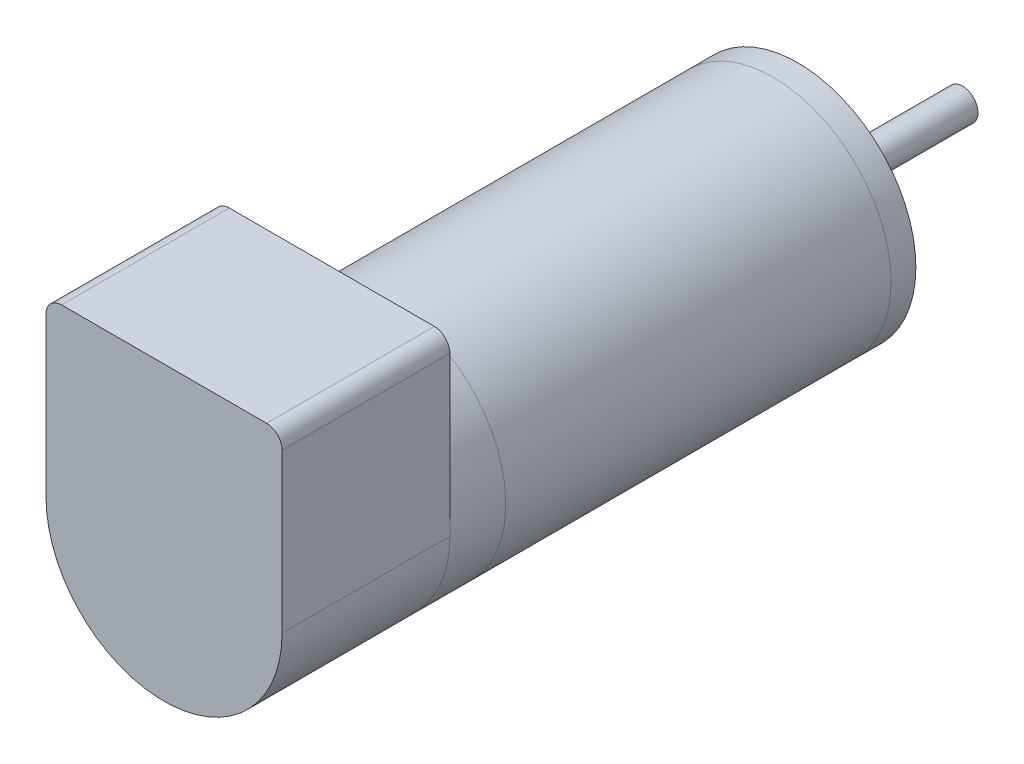
SolidWorks part; units mm, degrees
ref_plane "Front Plane" through (0, 0, 0) normal (0, 0, 1) x (1, 0, 0)
ref_plane "Top Plane" through (0, 0, 0) normal (0, 1, 0) x (1, 0, 0)
ref_plane "Right Plane" through (0, 0, 0) normal (1, 0, 0) x (0, 0, -1)
sketch "Sketch1" plane through (0, 0, 0) normal (1, 0, 0) x (0, 0, -1)
  line L0 (0, 0) -> (101.5, 0) construction
  line L1 (0, 0) -> (0, 19)
  line L2 (0, 19) -> (75, 19)
  line L3 (75, 19) -> (75, 6.25)
  line L4 (75, 6.25) -> (76.5, 6.25)
  line L5 (76.5, 6.25) -> (76.5, 2.5)
  line L6 (76.5, 2.5) -> (101.5, 2.5)
  line L7 (101.5, 2.5) -> (101.5, 0)
  line L8 (0, 0) -> (101.5, 0)
  point P5 (99.7203, 0)
  point P10 (79.7956, 2.5)
  dimension "D1" = 19
  dimension "D2" = 75
  dimension "D3" = 6.25
  dimension "D4" = 1.5
  dimension "D5" = 25
  dimension "D6" = 2.5
revolve "Revolve1" add sketch "Sketch1" angle 360 about L0
sketch "Sketch2" plane through (0, 0, 0) normal (0, 0, 1) x (1, 0, 0)
  line L0 (-19, 0) -> (-19, 25.5)
  line L1 (-16.5, 28) -> (16.5, 28)
  line L2 (19, 25.5) -> (19, 0)
  circle A0 centre (0, 0) radius 19 construction
  arc A1 (-19, 0) -> (19, 0) centre (0, 0) ccw
  arc A2 (19, 25.5) -> (16.5, 28) centre (16.5, 25.5) ccw
  arc A3 (-19, 25.5) -> (-16.5, 28) centre (-16.5, 25.5) cw
  point P5 (0, -19)
  dimension "D2" = 2.5
  dimension "D1" = 47
extrude "Boss-Extrude1" add sketch "Sketch2" along normal blind 27
sketch "Sketch3" plane through (0, 0, 0) normal (1, 0, 0) x (0, 0, -1)
  line L0 (71, 19) -> (71, -19)
  line L1 (-27, -19) -> (75, -19) construction
  line L2 (75, 19) -> (0, 19) construction
  line L3 (9, 19) -> (9, -19)
  line L4 (0, 19) -> (0, -19)
  line L5 (0, 25.5) -> (0, 0) construction
  line L6 (75, -19) -> (75, 19) construction
  point P15 (32.4701, 19)
  point P16 (32.6328, -19)
  dimension "D1" = 4
  dimension "D2" = 9
split line "Split Line1"
sketch "Sketch4" plane through (0, 0, -75) normal (0, 0, -1) x (-1, 0, 0)
  line L0 (-8.8388, 8.8388) -> (0, 0) construction
  line L1 (0, 0) -> (-19, 0) construction
  circle A0 centre (-8.8388, 8.8388) radius 1.5
  circle A1 centre (8.8388, 8.8388) radius 1.5
  circle A2 centre (8.8388, -8.8388) radius 1.5
  circle A3 centre (-8.8388, -8.8388) radius 1.5
  point P2 (0, 0)
  point P7 (-8.8388, -8.8388)
  point P15 (0, 0)
  dimension "D2" = 3
  dimension "D1" = 45
  dimension "D3" = 12.5
  dimension "D4" = 4
extrude "Cut-Extrude1" cut sketch "Sketch4" against normal blind 10
